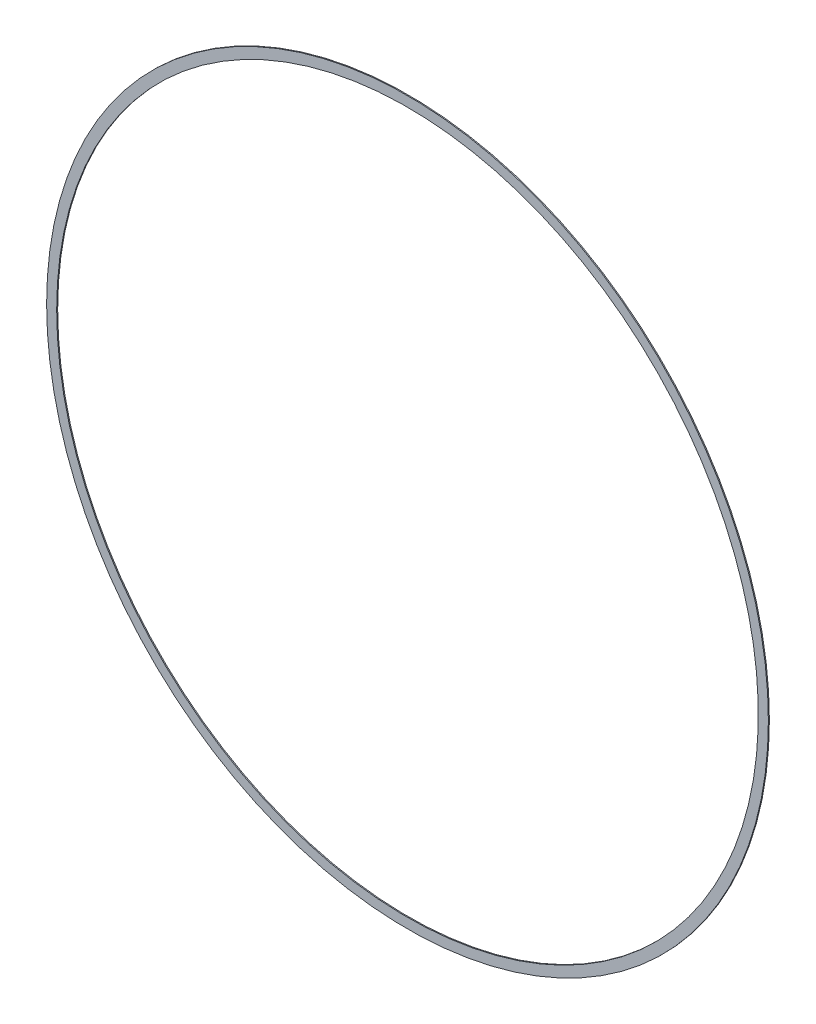
SolidWorks part; units mm, degrees
material "ASTM A36 Steel"
ref_plane "Front Plane" through (0, 0, 0) normal (0, 0, 1) x (1, 0, 0)
ref_plane "Top Plane" through (0, 0, 0) normal (0, 1, 0) x (1, 0, 0)
ref_plane "Right Plane" through (0, 0, 0) normal (1, 0, 0) x (0, 0, -1)
sketch "Sketch1" plane through (0, 0, 0) normal (0, 0, 1) x (1, 0, 0)
  circle A0 centre (0, 0) radius 1047
  dimension "D1" = 2094
extrude "Extrude-Thin1" add sketch "Sketch1" along normal blind 3 thin
